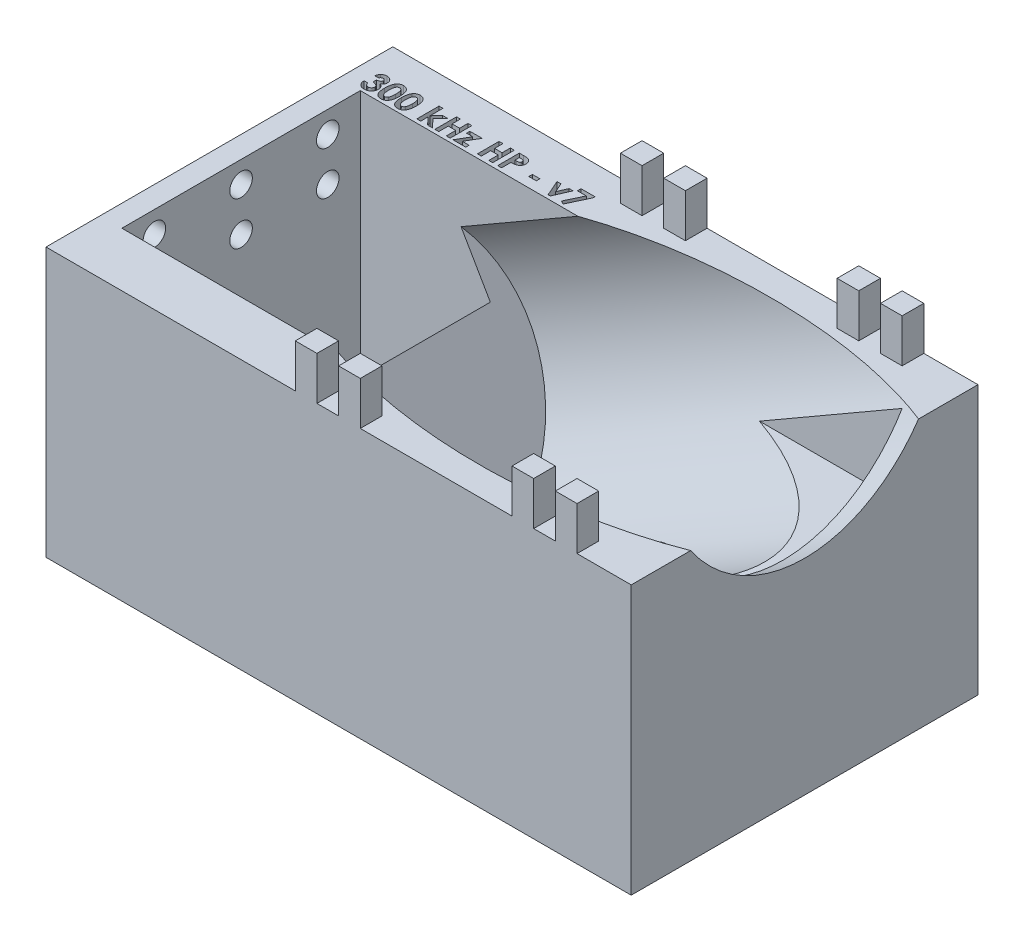
SolidWorks part; units mm, degrees
ref_plane "Front Plane" through (0, 0, 0) normal (0, 0, 1) x (1, 0, 0)
ref_plane "Top Plane" through (0, 0, 0) normal (0, 1, 0) x (1, 0, 0)
ref_plane "Right Plane" through (0, 0, 0) normal (1, 0, 0) x (0, 0, -1)
sketch "Sketch1" plane through (0, 0, 0) normal (0, 0, 1) x (1, 0, 0)
  line L1 (-139.7, -127) -> (88.9, -127)
  line L2 (-139.7, -127) -> (-139.7, 0)
  line L3 (-139.7, 0) -> (88.9, 0)
  line L4 (88.9, -127) -> (88.9, 0)
  line L5 (-139.7, -127) -> (88.9, 0) construction
  line L6 (-139.7, 0) -> (88.9, -127) construction
  point P0 (0, 0)
  dimension "D1" = 228.6
  dimension "D2" = 127
  dimension "D3" = 88.9
extrude "Boss-Extrude1" add sketch "Sketch1" along normal mid plane 101.6
sketch "Sketch10" plane through (0, -127, 0) normal (0, -1, 0) x (1, 0, 0)
  circle A0 centre (0, 0) radius 12.7
  dimension "D1" = 25.4
extrude "Cut-Extrude6" cut sketch "Sketch10" against normal through all
sketch "Sketch2" plane through (0, 0, 0) normal (0, 0, 1) x (1, 0, 0)
  line L0 (-66.2854, -40.8099) -> (0, -2.54) construction
  line L1 (0, 46.5867) -> (-66.0805, 8.4352)
  line L2 (-68.3029, -37.3155) -> (-87.5579, -3.9648)
  line L3 (-87.5579, -3.9648) -> (-66.0805, 8.4352)
  line L4 (-68.3029, -37.3155) -> (-66.2854, -40.8099)
  line L5 (-44.808, -28.4099) -> (-66.0805, 8.4352) construction
  line L7 (0, -2.54) -> (87.9882, 48.26)
  line L8 (-83.8, -2.54) -> (0, -2.54) construction
  line L10 (0, -2.54) -> (-66.2854, -40.8099)
  line L11 (88.9, 0) -> (-139.7, 0) construction
  line L12 (87.9882, 48.26) -> (66.7157, 85.1051)
  line L13 (0, 46.5867) -> (0, -2.54) construction
  line L17 (66.7157, 85.1051) -> (0, 46.5867)
  point P23 (-44.808, -28.4099)
  dimension "D1" = 30
  dimension "D2" = 24.8
  dimension "D3" = 2.54
  dimension "D4" = 51.7398
  dimension "D5" = 42.545
  dimension "D6" = 101.6
revolve "Cut-Revolve1" cut sketch "Sketch2" angle 360 about L0
sketch "Sketch11" plane through (0, -127, 0) normal (0, -1, 0) x (1, 0, 0)
  line L1 (13, 13) -> (-13, 13)
  line L2 (13, 13) -> (13, -13)
  line L3 (13, -13) -> (-13, -13)
  line L4 (-13, 13) -> (-13, -13)
  line L5 (13, 13) -> (-13, -13) construction
  line L6 (13, -13) -> (-13, 13) construction
  point P0 (0, 0)
  dimension "D1" = 26
sketch "Sketch13" plane through (0, 0, 0) normal (0, 1, 0) x (1, 0, 0)
  line L0 (88.9, 50.8) -> (-139.7, 50.8) construction
  line L1 (-41.275, 50.8) -> (-34.925, 50.8)
  line L2 (-41.275, 50.8) -> (-41.275, 44.45)
  line L3 (-41.275, 44.45) -> (-34.925, 44.45)
  line L4 (-34.925, 50.8) -> (-34.925, 44.45)
  line L5 (0, 0) -> (42.9001, 0) construction
  line L6 (-28.575, 50.8) -> (-22.225, 50.8)
  line L7 (-28.575, 50.8) -> (-28.575, 44.45)
  line L8 (-28.575, 44.45) -> (-22.225, 44.45)
  line L9 (-22.225, 50.8) -> (-22.225, 44.45)
  line L10 (0, 0) -> (0, -29.3087) construction
  line L11 (22.225, 50.8) -> (22.225, 44.45)
  line L12 (28.575, 44.45) -> (22.225, 44.45)
  line L13 (28.575, 50.8) -> (28.575, 44.45)
  line L14 (28.575, 50.8) -> (22.225, 50.8)
  line L15 (34.925, 50.8) -> (34.925, 44.45)
  line L16 (41.275, 44.45) -> (34.925, 44.45)
  line L17 (41.275, 50.8) -> (41.275, 44.45)
  line L18 (41.275, 50.8) -> (34.925, 50.8)
  line L19 (41.275, -50.8) -> (34.925, -50.8)
  line L20 (41.275, -50.8) -> (41.275, -44.45)
  line L21 (41.275, -44.45) -> (34.925, -44.45)
  line L22 (34.925, -50.8) -> (34.925, -44.45)
  line L23 (28.575, -50.8) -> (22.225, -50.8)
  line L24 (28.575, -50.8) -> (28.575, -44.45)
  line L25 (28.575, -44.45) -> (22.225, -44.45)
  line L26 (22.225, -50.8) -> (22.225, -44.45)
  line L27 (-22.225, -50.8) -> (-22.225, -44.45)
  line L28 (-28.575, -44.45) -> (-22.225, -44.45)
  line L29 (-28.575, -50.8) -> (-28.575, -44.45)
  line L30 (-28.575, -50.8) -> (-22.225, -50.8)
  line L31 (-34.925, -50.8) -> (-34.925, -44.45)
  line L32 (-41.275, -44.45) -> (-34.925, -44.45)
  line L33 (-41.275, -50.8) -> (-41.275, -44.45)
  line L34 (-41.275, -50.8) -> (-34.925, -50.8)
  point P18 (-25.4, 50.8)
  point P20 (-38.1, 50.8)
  dimension "D1" = 25.4
  dimension "D2" = 12.7
  dimension "D3" = 6.35
extrude "Boss-Extrude3" add sketch "Sketch13" along normal blind 12.7
sketch "Sketch22" plane through (0, 0, 0) normal (0, 1, 0) x (1, 0, 0)
  line L0 (-41.275, -50.8) -> (-139.7, -50.8) construction
  line L1 (-139.7, 50.8) -> (-114.3, 50.8)
  line L2 (-139.7, 50.8) -> (-139.7, -50.8)
  line L3 (-139.7, -50.8) -> (-114.3, -50.8)
  line L4 (-114.3, 50.8) -> (-114.3, -50.8)
  dimension "D1" = 25.4
extrude "Cut-Extrude17" cut sketch "Sketch22" against normal through all
sketch "Sketch23" plane through (0, -127, 0) normal (0, -1, 0) x (1, 0, 0)
  line L0 (-127, 127) -> (127, -127) construction
  line L1 (-127, 127) -> (127, 127)
  line L2 (-127, 127) -> (-127, -127)
  line L3 (-127, -127) -> (127, -127)
  line L4 (127, 127) -> (127, -127)
  dimension "D1" = 254
  dimension "D2" = 254
extrude "Cut-Extrude18" cut sketch "Sketch23" against normal blind 48.26
sketch "Sketch21" plane through (0, 0, 0) normal (0, 1, 0) x (1, 0, 0)
  line L1 (88.9, -50.8) -> (57.15, -50.8)
  line L2 (88.9, -50.8) -> (88.9, 50.8)
  line L3 (88.9, 50.8) -> (57.15, 50.8)
  line L4 (57.15, -50.8) -> (57.15, 50.8)
  line L5 (88.9, -50.8) -> (41.275, -50.8) construction
  line L6 (88.9, 50.8) -> (41.275, 50.8) construction
  line L7 (-114.3, -50.8) -> (-114.3, 50.8) construction
  dimension "D1" = 171.45
extrude "Cut-Extrude16" cut sketch "Sketch21" against normal through all
sketch "Sketch26" plane through (0, 0, 0) normal (0, 1, 0) x (1, 0, 0)
  line L0 (57.15, 50.8) -> (57.15, 33.3829) construction
  line L1 (-38.1, -34.925) -> (50.8, -34.925)
  line L2 (-38.1, -34.925) -> (-38.1, 34.925)
  line L3 (-38.1, 34.925) -> (50.8, 34.925)
  line L4 (50.8, -34.925) -> (50.8, 34.925)
  line L5 (-114.3, -50.8) -> (-114.3, 50.8) construction
  point P4 (-38.1, 0)
  dimension "D1" = 6.35
  dimension "D2" = 76.2
  dimension "D3" = 69.85
extrude "Cut-Extrude21" cut sketch "Sketch26" against normal blind 25.4
sketch "Sketch27" plane through (-114.3, 0, 0) normal (-1, 0, 0) x (0, 0, 1)
  line L0 (50.8, 0) -> (-50.8, 0) construction
  line L1 (-25.4, -6.35) -> (25.4, -6.35) construction
  line L2 (-25.4, -6.35) -> (-25.4, -19.05) construction
  line L3 (-25.4, -19.05) -> (25.4, -19.05) construction
  line L4 (25.4, -6.35) -> (25.4, -19.05) construction
  line L7 (-25.4, -19.05) -> (-25.4, -31.75) construction
  line L8 (-25.4, -31.75) -> (25.4, -31.75) construction
  line L9 (25.4, -19.05) -> (25.4, -31.75) construction
  circle A0 centre (-25.4, -6.35) radius 3.302
  circle A1 centre (0, -6.35) radius 3.302
  circle A2 centre (0, -19.05) radius 3.302
  circle A3 centre (25.4, -6.35) radius 3.302
  circle A4 centre (25.4, -19.05) radius 3.302
  circle A5 centre (-25.4, -19.05) radius 3.302
  circle A7 centre (-25.4, -31.75) radius 3.302 [skipped]
  circle A8 centre (0, -31.75) radius 3.302 [skipped]
  circle A9 centre (25.4, -31.75) radius 3.302 [skipped]
  point P4 (0, -6.35)
  dimension "D5" = 6.604
  dimension "D8" = 25.4
  dimension "D1" = 50.8
  dimension "D2" = 12.7
  dimension "D3" = 6.35
  dimension "D4" = 12.7
  dimension "D6" = 3
  dimension "D7" = 3
extrude "Cut-Extrude22" cut sketch "Sketch27" against normal blind 25.4 and the other way through all
sketch "Sketch28" plane through (0, 0, 0) normal (0, 1, 0) x (1, 0, 0)
  line L0 (-114.3, 36.0198) -> (-43.5568, 36.0198) construction
  line L3 (-114.3, -50.8) -> (-114.3, 50.8) construction
  text T0 "<b>300 kHz HP - v7</b>" font "Century Gothic" height 6.35
extrude "Cut-Extrude23" cut sketch "Sketch28" against normal blind 3.175
sketch "Sketch30" plane through (0, -25.4, 0) normal (0, 1, 0) x (1, 0, 0)
  circle A0 centre (-95.25, 25.4) radius 3.429
  circle A2 centre (-82.55, 25.4) radius 3.429
  circle A3 centre (-82.55, 12.7) radius 3.429
  circle A4 centre (-82.55, 0) radius 3.429
  circle A5 centre (-82.55, -12.7) radius 3.429
  circle A6 centre (-82.55, -25.4) radius 3.429
  circle A7 centre (-95.25, 12.7) radius 3.429
  circle A8 centre (-95.25, 0) radius 3.429
  circle A9 centre (-95.25, -12.7) radius 3.429
  circle A10 centre (-95.25, -25.4) radius 3.429
  dimension "D1" = 6.858
  dimension "D2" = 25.4
  dimension "D3" = 95.25
  dimension "D4" = 2
  dimension "D5" = 5
extrude "Cut-Extrude24" cut sketch "Sketch30" against normal through all
sketch "Sketch31" plane through (0, -25.4, 0) normal (0, 1, 0) x (1, 0, 0)
  line L0 (-107.95, -34.925) -> (-44.1937, -34.925) construction
  line L1 (-107.95, 34.925) -> (-69.85, 34.925)
  line L2 (-107.95, 34.925) -> (-107.95, -34.925)
  line L3 (-107.95, -34.925) -> (-69.85, -34.925)
  line L4 (-69.85, 34.925) -> (-69.85, -34.925)
  line L5 (-114.3, -50.8) -> (-114.3, 50.8) construction
  line L6 (-41.275, 50.8) -> (-114.3, 50.8) construction
  point P7 (0, 0)
  dimension "D1" = 38.1
  dimension "D2" = 6.35
  dimension "D3" = 15.875
extrude "Cut-Extrude25" cut sketch "Sketch31" against normal offset from surface 6.35 and the other way through all up to face at (-82.55, -78.74, 28.829)
sketch "Sketch32" plane through (0, 0, 0) normal (0, 1, 0) x (1, 0, 0)
  line L0 (-107.95, -34.925) -> (-69.85, -34.925) construction
  line L1 (-69.85, 34.925) -> (-35.0736, 34.925)
  line L2 (-69.85, 34.925) -> (-69.85, -34.925)
  line L3 (-69.85, -34.925) -> (-35.0736, -34.925)
  line L4 (-35.0736, 34.925) -> (-35.0736, -34.925)
extrude "Cut-Extrude26" cut sketch "Sketch32" against normal up to next
